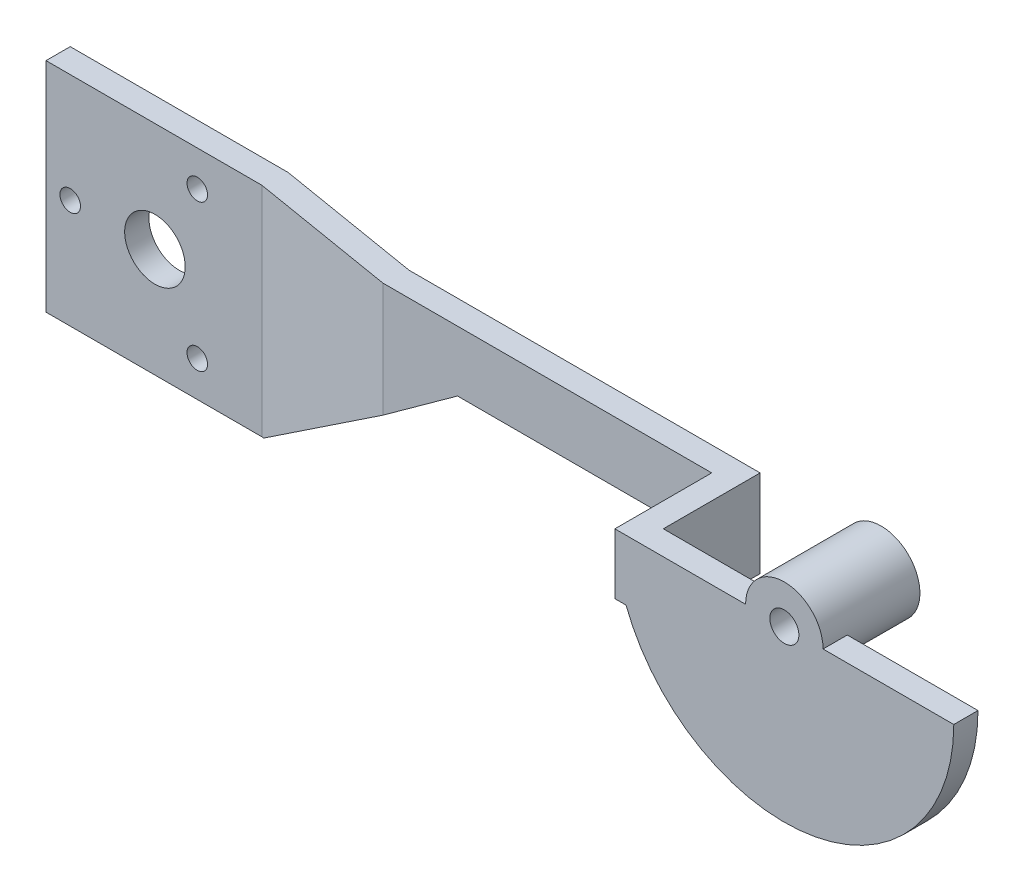
SolidWorks part; units mm, degrees
ref_plane "GAUCHE" through (0, 0, 0) normal (0, 0, 1) x (1, 0, 0)
ref_plane "Plan2" through (0, 0, 0) normal (0, 1, 0) x (1, 0, 0)
ref_plane "Plan3" through (0, 0, 0) normal (1, 0, 0) x (0, 0, -1)
sketch "Esquisse1" plane through (0, 0, 0) normal (0, 0, 1) x (1, 0, 0)
  line L0 (380, 45) -> (326, 45)
  line L1 (-45, 45) -> (-45, -45)
  line L2 (-45, -45) -> (45, -45)
  line L3 (45, -45) -> (135, 20)
  line L4 (135, 20) -> (244.6165, 20)
  line L11 (294, 45) -> (-45, 45)
  arc A0 (244.6165, 20) -> (380, 45) centre (310, 45) ccw
  arc A1 (326, 45) -> (294, 45) centre (310, 45) ccw
  circle A2 centre (310, 45) radius 6
  circle A3 centre (-35, 0) radius 4.25
  circle A4 centre (17.5, 30.3109) radius 4.25
  circle A5 centre (17.5, -30.3109) radius 4.25
  dimension "D8" = 12
  dimension "D10" = 70
  dimension "D11" = 8.5
  dimension "D15" = 60.6218
  dimension "D16" = 35
  dimension "D17" = 35
  dimension "D9" = 16
  dimension "D12" = 8.5
  dimension "D13" = 8.5
  dimension "D1" = 90
  dimension "D2" = 90
  dimension "D3" = 45
  dimension "D4" = 45
  dimension "D5" = 25
  dimension "D6" = 90
  dimension "D7" = 310
  dimension "D14" = 35
extrude "Base-Extrusion" add sketch "Esquisse1" along normal blind 60
sketch "Esquisse2" plane through (0, 45, 0) normal (0, 1, 0) x (-1, 0, 0)
  line L0 (-294, 50) -> (-294, 10)
  line L1 (-294, 60) -> (-294, 0) construction
  line L2 (-294, 50) -> (-250, 50)
  line L3 (-250, 50) -> (-250, 10)
  line L4 (-250, 10) -> (-105, 10)
  line L5 (-105, 10) -> (-45, 0)
  line L6 (-294, 0) -> (45, 0) construction
  line L7 (-45, 0) -> (-380, 0)
  line L8 (-380, 0) -> (-380, 50)
  line L9 (-380, 60) -> (-380, 0) construction
  line L10 (-380, 50) -> (-326, 50)
  line L11 (-326, 60) -> (-326, 0) construction
  line L12 (-326, 50) -> (-326, 10)
  line L13 (-326, 10) -> (-294, 10)
  line L15 (-240, 60) -> (-240, 20)
  line L16 (-294, 60) -> (45, 60) construction
  line L17 (-240, 20) -> (-104.1724, 20)
  line L18 (-104.1724, 20) -> (-44.1724, 10)
  line L19 (-44.1724, 10) -> (45, 10)
  line L20 (45, 60) -> (45, 0) construction
  line L21 (45, 10) -> (45, 60)
  line L22 (45, 60) -> (-240, 60)
  line L23 (-380, 60) -> (-326, 60) construction
  dimension "D1" = 285
  dimension "D2" = 10
  dimension "D3" = 10
  dimension "D4" = 10
  dimension "D5" = 90
  dimension "D6" = 150
  dimension "D7" = 10
  dimension "D8" = 10
  dimension "D9" = 10
  dimension "D10" = 10
  dimension "D11" = 10
extrude "Enlèv. mat.-Extru.1" cut sketch "Esquisse2" against normal through all
sketch "Esquisse3" plane through (0, 0, 0) normal (0, 0, -1) x (-1, 0, 0)
  line L2 (-304, 45) -> (-294, 45)
  line L3 (-326, 45) -> (-316, 45)
  line L4 (-304, 45) -> (-294, 45)
  line L5 (-326, 45) -> (-316, 45)
  arc A2 (-294, 45) -> (-326, 45) centre (-310, 45) ccw
  arc A3 (-304, 45) -> (-316, 45) centre (-310, 45) ccw
  arc A4 (-294, 45) -> (-326, 45) centre (-310, 45) ccw
  arc A5 (-304, 45) -> (-316, 45) centre (-310, 45) ccw
  dimension "D1" = 0
extrude "Enlèv. mat.-Extru.2" cut sketch "Esquisse3" against normal blind 10
sketch "Esquisse4" plane through (0, 0, 10) normal (0, 0, -1) x (-1, 0, 0)
  line L2 (-294, -23.1469) -> (-294, 45)
  line L3 (-326, 45) -> (-326, -23.1469)
  line L4 (-294, -23.1469) -> (-294, 45)
  line L5 (-326, 45) -> (-326, -23.1469)
  arc A0 (-326, 45) -> (-294, 45) centre (-310, 45) ccw
  arc A2 (-294, 45) -> (-326, 45) centre (-310, 45) ccw
  arc A3 (-326, -23.1469) -> (-294, -23.1469) centre (-310, 45) ccw
  arc A5 (-326, -23.1469) -> (-294, -23.1469) centre (-310, 45) ccw
  dimension "D1" = 0
extrude "Enlèv. mat.-Extru.3" cut sketch "Esquisse4" against normal blind 40
sketch "Esquisse5" plane through (0, 0, 10) normal (0, 0, 1) x (1, 0, 0)
  circle A0 centre (0, 0) radius 12.5
  dimension "D1" = 25
extrude "Enlèv. mat.-Extru.4" cut sketch "Esquisse5" against normal through all
sketch "Esquisse6" plane through (0, 0, 10) normal (0, 0, -1) x (-1, 0, 0)
  circle A0 centre (-310, 45) radius 16
  circle A1 centre (-310, 45) radius 6
  circle A2 centre (-310, 45) radius 6 construction
  dimension "D1" = 12
  dimension "D2" = 32
extrude "Enlèv. mat.-Extru.5" cut sketch "Esquisse6" against normal blind 10
